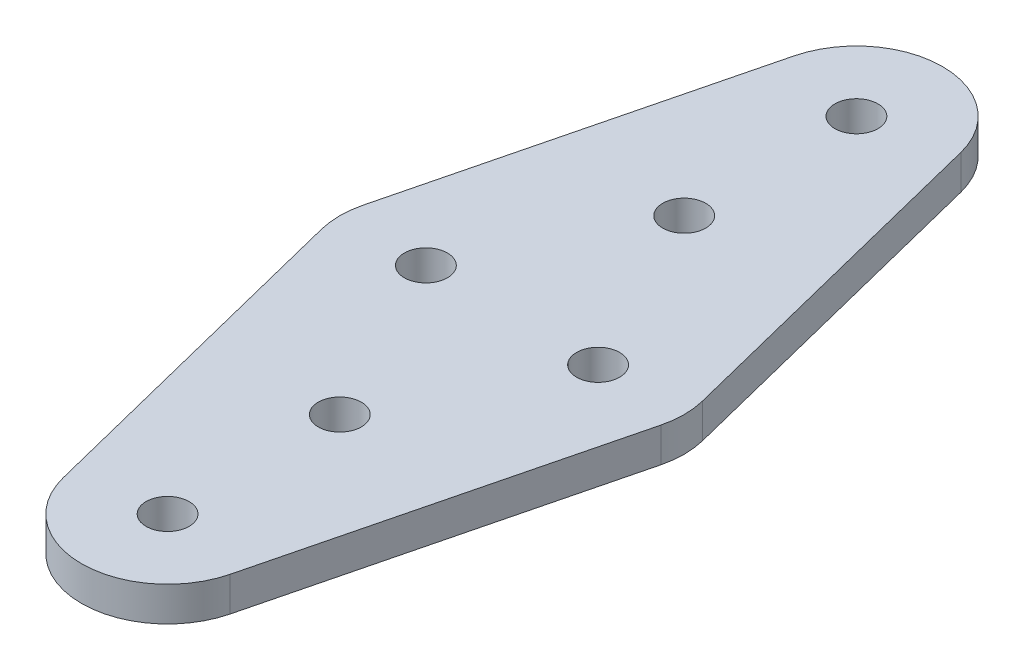
SolidWorks part; units mm, degrees
material "Thornel Mat VMA"
ref_plane "Front Plane" through (0, 0, 0) normal (0, 0, 1) x (1, 0, 0)
ref_plane "Top Plane" through (0, 0, 0) normal (0, 1, 0) x (1, 0, 0)
ref_plane "Right Plane" through (0, 0, 0) normal (1, 0, 0) x (0, 0, -1)
sketch "Sketch1" plane through (0, 0, 0) normal (0, 1, 0) x (1, 0, 0)
  line L0 (0, 48.5704) -> (0, -31.4177) construction
  line L1 (-41.6317, 0) -> (40.9422, 0) construction
  line L2 (-9.7014, 42.4254) -> (-19.7014, 2.4254)
  line L4 (9.7014, 42.4254) -> (19.7014, 2.4254)
  line L5 (9.7014, -42.4254) -> (19.7014, -2.4254)
  line L6 (-9.7014, -42.4254) -> (-19.7014, -2.4254)
  circle A0 centre (10, 0) radius 2.5
  circle A1 centre (-10, 0) radius 2.5
  circle A2 centre (0, 20) radius 2.5
  circle A3 centre (0, 40) radius 2.5
  arc A4 (9.7014, 42.4254) -> (-9.7014, 42.4254) centre (0, 40) ccw
  arc A5 (-19.7014, 2.4254) -> (-19.7014, -2.4254) centre (-10, 0) ccw
  arc A6 (19.7014, -2.4254) -> (19.7014, 2.4254) centre (10, 0) ccw
  circle A7 centre (0, -20) radius 2.5
  circle A8 centre (0, -40) radius 2.5
  arc A9 (9.7014, -42.4254) -> (-9.7014, -42.4254) centre (0, -40) cw
  dimension "D1" = 5
  dimension "D3" = 5
  dimension "D5" = 5
  dimension "D7" = 20
  dimension "D8" = 20
  dimension "D9" = 20
  dimension "D2" = 10
  dimension "D4" = 20
  dimension "D6" = 40
extrude "Boss-Extrude1" add sketch "Sketch1" along normal blind 4
